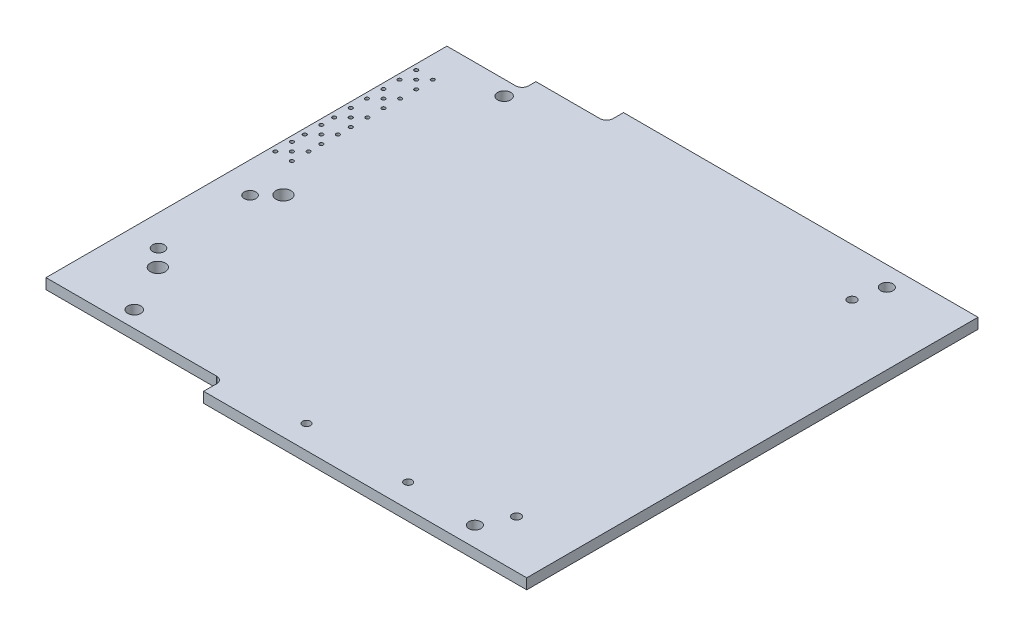
SolidWorks part; units mm, degrees
ref_plane "Front Plane" through (0, 0, 0) normal (0, 0, 1) x (1, 0, 0)
ref_plane "Top Plane" through (0, 0, 0) normal (0, 1, 0) x (1, 0, 0)
ref_plane "Right Plane" through (0, 0, 0) normal (1, 0, 0) x (0, 0, -1)
sketch "Sketch2" plane through (0, 0, 0) normal (0, 1, 0) x (1, 0, 0)
  line L0 (10.9, -3) -> (10.9, 66)
  line L1 (10.9, 66) -> (-43.3, 66)
  line L2 (-43.3, 66) -> (-43.3, 64.4)
  line L3 (-44.3, 63.4) -> (-54.1, 63.4)
  line L4 (-54.1, 63.4) -> (-54.1, 62.3)
  line L5 (-55.1, 61.3) -> (-65.6, 61.3)
  line L6 (-65.6, 61.3) -> (-65.6, 0)
  line L7 (-65.6, 0) -> (-39.5, 0)
  line L8 (-38.5, -1) -> (-38.5, -3)
  line L9 (-38.5, -3) -> (10.9, -3)
  circle A0 centre (-60.9, 12.5) radius 0.9
  circle A1 centre (-60.9, 26.5) radius 0.9
  circle A2 centre (-58.4, 9.9) radius 1.15
  circle A3 centre (-58.4, 29.1) radius 1.15
  circle A4 centre (-64.77, 43.23) radius 0.28
  circle A5 centre (-64.77, 43.23) radius 0.28
  circle A6 centre (-62.23, 43.23) radius 0.28
  circle A7 centre (-62.23, 43.23) radius 0.28
  circle A8 centre (-62.23, 45.77) radius 0.28
  circle A9 centre (-62.23, 45.77) radius 0.28
  circle A10 centre (-64.77, 45.77) radius 0.28
  circle A11 centre (-64.77, 45.77) radius 0.28
  circle A12 centre (-63.5, 44.5) radius 0.28
  circle A13 centre (-63.5, 44.5) radius 0.28
  circle A14 centre (-64.77, 38.73) radius 0.28
  circle A15 centre (-64.77, 38.73) radius 0.28
  circle A16 centre (-62.23, 38.73) radius 0.28
  circle A17 centre (-62.23, 38.73) radius 0.28
  circle A18 centre (-62.23, 41.27) radius 0.28
  circle A19 centre (-62.23, 41.27) radius 0.28
  circle A20 centre (-64.77, 41.27) radius 0.28
  circle A21 centre (-64.77, 41.27) radius 0.28
  circle A22 centre (-63.5, 40) radius 0.28
  circle A23 centre (-63.5, 40) radius 0.28
  circle A24 centre (-64.77, 34.23) radius 0.28
  circle A25 centre (-64.77, 34.23) radius 0.28
  circle A26 centre (-62.23, 34.23) radius 0.28
  circle A27 centre (-62.23, 34.23) radius 0.28
  circle A28 centre (-62.23, 36.77) radius 0.28
  circle A29 centre (-62.23, 36.77) radius 0.28
  circle A30 centre (-64.77, 36.77) radius 0.28
  circle A31 centre (-64.77, 36.77) radius 0.28
  circle A32 centre (-63.5, 35.5) radius 0.28
  circle A33 centre (-63.5, 35.5) radius 0.28
  circle A34 centre (-26.37, 0.6) radius 0.595
  circle A35 centre (-10.83, 0.6) radius 0.595
  arc A36 (10.9318, 66) -> (10.8682, 66) centre (10.9, 66) ccw
  arc A37 (10.8682, -3) -> (10.9318, -3) centre (10.9, -3) ccw
  arc A38 (-43.3, 66.0318) -> (-43.3, 65.9682) centre (-43.3, 66) ccw
  arc A39 (10.9, 65.9682) -> (10.9, 66.0318) centre (10.9, 66) ccw
  arc A40 (-43.3318, 64.4) -> (-43.2683, 64.4) centre (-43.3001, 64.4) ccw
  arc A41 (-43.2683, 66) -> (-43.3318, 66) centre (-43.3001, 66) ccw
  arc A42 (-44.3, 63.4) -> (-43.3, 64.4) centre (-44.3, 64.4) ccw
  arc A43 (-44.3, 63.4318) -> (-44.3, 63.3683) centre (-44.3, 63.4001) ccw
  arc A44 (-43.2683, 64.4) -> (-43.3318, 64.4) centre (-43.3001, 64.4) ccw
  arc A45 (-54.1, 63.4318) -> (-54.1, 63.3683) centre (-54.1, 63.4001) ccw
  arc A46 (-44.3, 63.3683) -> (-44.3, 63.4318) centre (-44.3, 63.4001) ccw
  arc A47 (-54.1318, 62.3) -> (-54.0682, 62.3) centre (-54.1, 62.3) ccw
  arc A48 (-54.0682, 63.4) -> (-54.1318, 63.4) centre (-54.1, 63.4) ccw
  arc A49 (-55.1, 61.3) -> (-54.1, 62.3) centre (-55.1, 62.3) ccw
  arc A50 (-55.1, 61.3318) -> (-55.1, 61.2683) centre (-55.1, 61.3001) ccw
  arc A51 (-54.0682, 62.3) -> (-54.1318, 62.3) centre (-54.1, 62.3) ccw
  arc A52 (-65.6, 61.3318) -> (-65.6, 61.2683) centre (-65.6, 61.3001) ccw
  arc A53 (-55.1, 61.2683) -> (-55.1, 61.3318) centre (-55.1, 61.3001) ccw
  arc A54 (-65.6318, 0) -> (-65.5683, 0) centre (-65.6, 0) ccw
  arc A55 (-65.5683, 61.3) -> (-65.6318, 61.3) centre (-65.6, 61.3) ccw
  arc A56 (-39.5, -0.0318) -> (-39.5, 0.0318) centre (-39.5, 0) ccw
  arc A57 (-65.6, 0.0318) -> (-65.6, -0.0318) centre (-65.6, 0) ccw
  arc A58 (-38.5, -1) -> (-39.5, 0) centre (-39.5, -1) ccw
  arc A59 (-38.5318, -1) -> (-38.4682, -1) centre (-38.5, -1) ccw
  arc A60 (-39.5, 0.0318) -> (-39.5, -0.0318) centre (-39.5, 0) ccw
  arc A61 (-38.5318, -3) -> (-38.4682, -3) centre (-38.5, -3) ccw
  arc A62 (-38.4682, -1) -> (-38.5318, -1) centre (-38.5, -1) ccw
  arc A63 (10.9, -3.0318) -> (10.9, -2.9682) centre (10.9, -3) ccw
  arc A64 (-38.5, -2.9682) -> (-38.5, -3.0318) centre (-38.5, -3) ccw
  circle A65 centre (-54.6, 59.05) radius 1
  circle A66 centre (-54.6, 59.05) radius 1
  circle A67 centre (-54.6, 2.5) radius 1
  circle A68 centre (-54.6, 2.5) radius 1
  circle A69 centre (2, 4.3347) radius 0.6604
  circle A70 centre (-1.05, 58.6907) radius 0.6604
  circle A71 centre (-0.032, 62.996) radius 0.9271
  circle A72 centre (-0.032, 62.996) radius 0.9271
  circle A73 centre (-0.032, 0.004) radius 0.9271
  circle A74 centre (-0.032, 0.004) radius 0.9271
  circle A75 centre (-64.77, 53.23) radius 0.28
  circle A76 centre (-64.77, 53.23) radius 0.28
  circle A77 centre (-62.23, 53.23) radius 0.28
  circle A78 centre (-62.23, 53.23) radius 0.28
  circle A79 centre (-62.23, 55.77) radius 0.28
  circle A80 centre (-62.23, 55.77) radius 0.28
  circle A81 centre (-64.77, 55.77) radius 0.28
  circle A82 centre (-64.77, 55.77) radius 0.28
  circle A83 centre (-63.5, 54.5) radius 0.28
  circle A84 centre (-63.5, 54.5) radius 0.28
  circle A85 centre (-64.77, 48.23) radius 0.28
  circle A86 centre (-64.77, 48.23) radius 0.28
  circle A87 centre (-62.23, 48.23) radius 0.28
  circle A88 centre (-62.23, 48.23) radius 0.28
  circle A89 centre (-62.23, 50.77) radius 0.28
  circle A90 centre (-62.23, 50.77) radius 0.28
  circle A91 centre (-64.77, 50.77) radius 0.28
  circle A92 centre (-64.77, 50.77) radius 0.28
  circle A93 centre (-63.5, 49.5) radius 0.28
  circle A94 centre (-63.5, 49.5) radius 0.28
extrude "Boss-Extrude1" add sketch "Sketch2" along normal blind 1.6 contours A62 A59 L8 L9 L0 L1 L2 A44 A40 A42 A46 A43 L3 L4 A51 A47 A49 A53 A50 L5 L6 L7 A60 A56 A58 A93 A91 A89 A87 A85 A83
